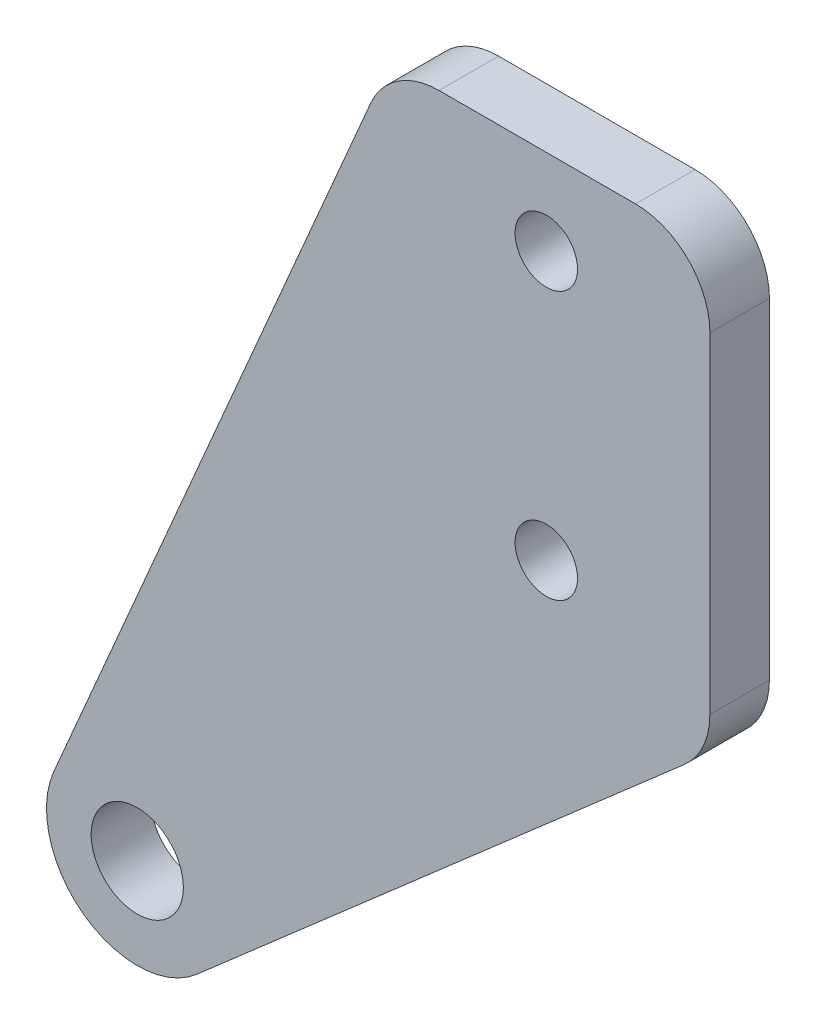
SolidWorks part; units mm, degrees
material "Thornel Mat VMA"
ref_plane "前视基准面" through (0, 0, 0) normal (0, 0, 1) x (1, 0, 0)
ref_plane "上视基准面" through (0, 0, 0) normal (0, 1, 0) x (1, 0, 0)
ref_plane "右视基准面" through (0, 0, 0) normal (1, 0, 0) x (0, 0, -1)
other "Configuration Table"
sketch "草图2" plane through (0, 0, 0) normal (0, 0, 1) x (1, 0, 0)
  line L0 (0, 0) -> (50000, 0) construction
  line L1 (-4, -9) -> (4, -9) construction
  line L2 (-4, -9) -> (-4, 9) construction
  line L3 (-4, 9) -> (4, 9) construction
  line L4 (4, -9) -> (4, 9) construction
  line L5 (-4, -9) -> (4, 9) construction
  line L6 (-4, 9) -> (4, -9) construction
  line L7 (-14.5, 14.75) -> (-37.1043, -37.8412)
  line L8 (-14.5, -14.75) -> (7, -14.75)
  line L9 (-14.5, -14.75) -> (-14.5, 14.75)
  line L10 (-14.5, 14.75) -> (7, 14.75)
  line L11 (7, -14.75) -> (7, 14.75)
  line L12 (-14.5, -14.75) -> (7, 14.75) construction
  line L13 (-14.5, 14.75) -> (7, -14.75) construction
  line L14 (-27.4893, -44.8461) -> (7, -14.75)
  circle A0 centre (-4, 9) radius 2.1
  circle A3 centre (-4, -9) radius 2.1
  arc A4 (-37.1043, -37.8412) -> (-27.4893, -44.8461) centre (-31.5, -40.25) ccw
  circle A5 centre (-31.5, -40.25) radius 3.1
  point P0 (0, 0)
  point P12 (-3.75, 0)
  dimension "D3" = 4.2
  dimension "D7" = 3
  dimension "D8" = 6.2
  dimension "D1" = 8
  dimension "D2" = 18
  dimension "D4" = 10.5
  dimension "D5" = 29.5
  dimension "D6" = 3
  dimension "D9" = 55
  dimension "D10" = 17
extrude "凸台-拉伸1" add sketch "草图2" along normal blind 4
fillet "圆角1" radius 5 3 edges at (7, 14.75, 2) (7, -14.75, 2) (-14.5, 14.75, 2)
